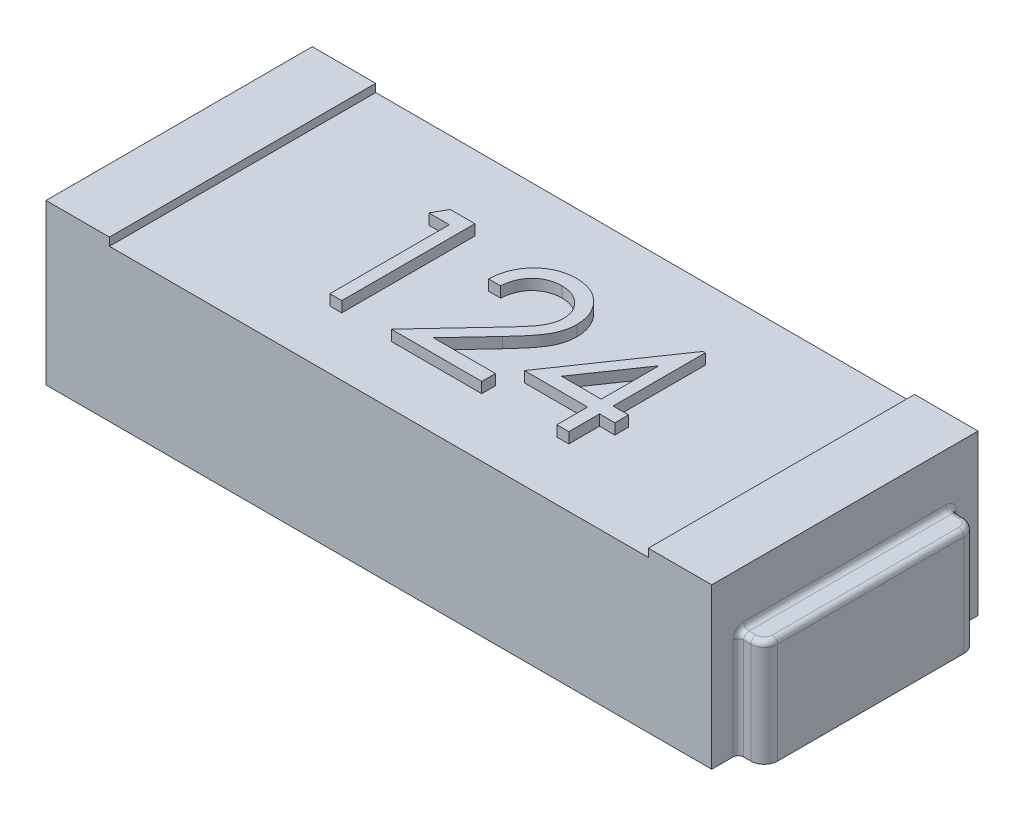
SolidWorks part; units mm, degrees
ref_plane "Plan de face" through (0, 0, 0) normal (0, 0, 1) x (1, 0, 0)
ref_plane "Plan de dessus" through (0, 0, 0) normal (0, 1, 0) x (1, 0, 0)
ref_plane "Plan de droite" through (0, 0, 0) normal (1, 0, 0) x (0, 0, -1)
sketch "Esquisse1" plane through (0, 0, 0) normal (0, 1, 0) x (1, 0, 0)
  line L1 (1.25, -0.5) -> (-1.25, -0.5)
  line L2 (1.25, -0.5) -> (1.25, 0.5)
  line L3 (1.25, 0.5) -> (-1.25, 0.5)
  line L4 (-1.25, -0.5) -> (-1.25, 0.5)
  line L5 (1.25, -0.5) -> (-1.25, 0.5) construction
  line L6 (1.25, 0.5) -> (-1.25, -0.5) construction
  point P0 (0, 0)
  dimension "D1" = 2.5
  dimension "D2" = 1
extrude "Boss.-Extru.1" add sketch "Esquisse1" along normal blind 0.6
sketch "Esquisse2" plane through (0, 0.6, 0) normal (0, 1, 0) x (1, 0, 0)
  line L0 (1.25, 0.5) -> (-1.25, 0.5) construction
  line L1 (1.0118, -0.5) -> (-1.0118, -0.5)
  line L2 (1.0118, -0.5) -> (1.0118, 0.5)
  line L3 (1.0118, 0.5) -> (-1.0118, 0.5)
  line L4 (-1.0118, -0.5) -> (-1.0118, 0.5)
  line L5 (1.0118, -0.5) -> (-1.0118, 0.5) construction
  line L6 (1.0118, 0.5) -> (-1.0118, -0.5) construction
  point P0 (0, 0)
extrude "Enlèv. mat.-Extru.1" cut sketch "Esquisse2" against normal blind 0.03
sketch "Esquisse3" plane through (0, 0, 0) normal (0, 1, 0) x (1, 0, 0)
  line L0 (1.25, -0.5) -> (1.25, 0.5) construction
  line L1 (1.25, 0.4) -> (1.2971, 0.4)
  line L2 (1.25, 0.4) -> (1.25, -0.4)
  line L3 (1.25, -0.4) -> (1.2971, -0.4)
  line L4 (1.3471, 0.35) -> (1.3471, -0.35)
  line L5 (1.25, 0.5) -> (1.0118, 0.5) construction
  line L6 (1.0118, -0.5) -> (1.25, -0.5) construction
  arc A0 (1.2971, -0.4) -> (1.3471, -0.35) centre (1.2971, -0.35) ccw
  arc A1 (1.2971, 0.4) -> (1.3471, 0.35) centre (1.2971, 0.35) cw
  dimension "D1" = 0.05
  dimension "D2" = 0.1
  dimension "D3" = 0.1
extrude "Boss.-Extru.2" add sketch "Esquisse3" along normal blind 0.4
fillet "Congé1" radius 0.02 8 edges at (1.25, 0.2, -0.4) (1.25, 0.2, 0.4) (1.2736, 0.4, -0.4) (1.3325, 0.4, -0.3854) (1.3471, 0.4, 0) (1.3325, 0.4, 0.3854) (1.2736, 0.4, 0.4) (1.25, 0.4, 0)
mirror "Symétrie2" about plane through (0, 0, 0) normal (1, 0, 0) of "Congé1", "Boss.-Extru.2"
sketch "Esquisse4" plane through (0, 0.57, 0) normal (0, 1, 0) x (1, 0, 0)
  line L0 (0.7576, -0.2803) -> (-0.7576, -0.2803) construction
  text T0 "124\r\n\r\n" font "Century Gothic" height 0.5
  point P3 (0, -0.2803)
extrude "Boss.-Extru.3" add sketch "Esquisse4" along normal blind 0.04
